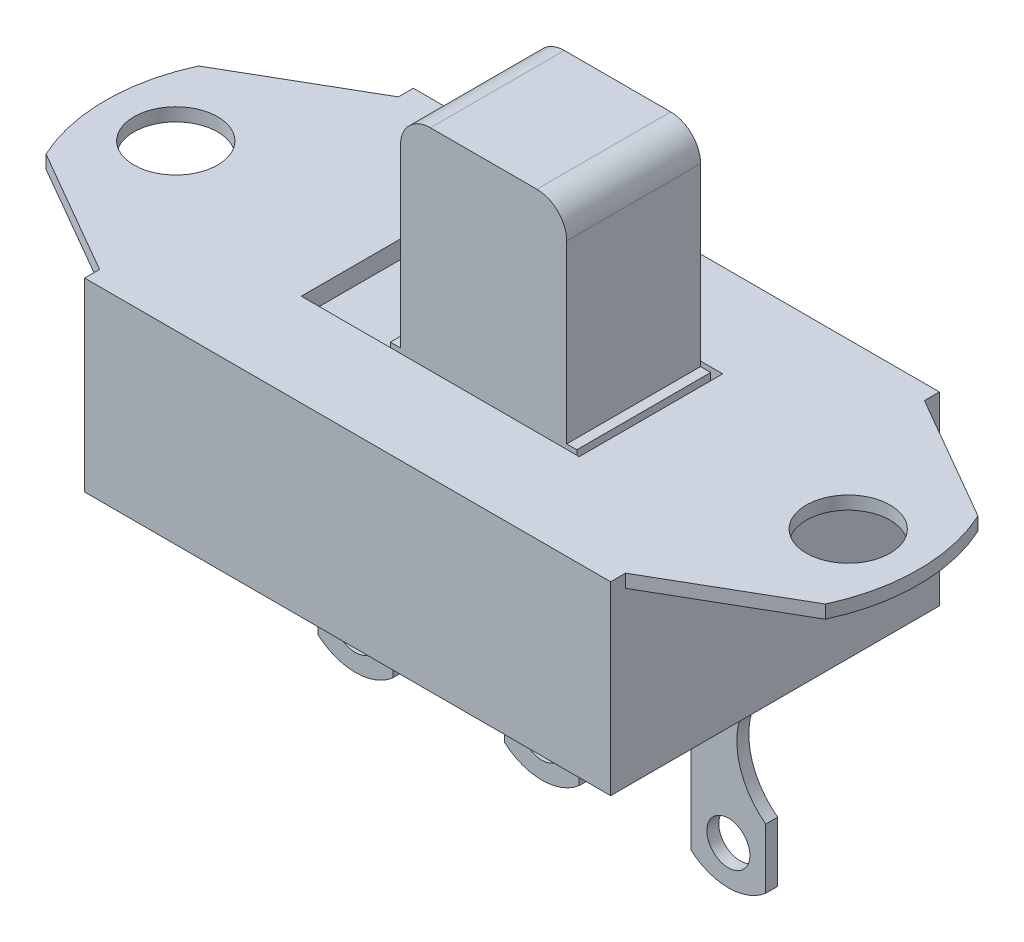
SolidWorks part; units mm, degrees
ref_plane "Front Plane" through (0, 0, 0) normal (0, 0, 1) x (1, 0, 0)
ref_plane "Top Plane" through (0, 0, 0) normal (0, 1, 0) x (1, 0, 0)
ref_plane "Right Plane" through (0, 0, 0) normal (1, 0, 0) x (0, 0, -1)
sketch "Sketch1" plane through (0, 0, 0) normal (0, 0, 1) x (1, 0, 0)
  line L1 (0, 0) -> (22.352, 0)
  line L2 (0, 0) -> (0, 7.874)
  line L3 (0, 7.874) -> (22.352, 7.874)
  line L4 (22.352, 0) -> (22.352, 7.874)
  dimension "D1" = 22.352
  dimension "D2" = 7.874
extrude "Extrude1" add sketch "Sketch1" along normal mid plane 13.97
sketch "Sketch2" plane through (0, 7.874, 0) normal (0, 1, 0) x (1, 0, 0)
  line L0 (0, 6.35) -> (-5.3848, 3.2411)
  line L1 (0, -6.985) -> (0, 6.985) construction
  line L2 (-6.096, 6.4274) -> (-6.096, -6.7131) construction
  line L3 (11.176, 6.985) -> (11.176, -6.985) construction
  line L4 (22.352, 6.985) -> (0, 6.985) construction
  line L5 (22.352, -6.985) -> (0, -6.985) construction
  line L6 (0, 0) -> (-8.6981, 0) construction
  line L7 (0, -6.35) -> (-5.3848, -3.2411)
  line L8 (0, 6.35) -> (0, -6.35)
  line L9 (22.352, 6.35) -> (22.352, -6.35)
  line L10 (22.352, -6.35) -> (27.7368, -3.2411)
  line L11 (22.352, 6.35) -> (27.7368, 3.2411)
  arc A0 (-5.3848, 3.2411) -> (-5.3848, -3.2411) centre (1.6447, 0) ccw
  arc A1 (27.7368, 3.2411) -> (27.7368, -3.2411) centre (20.7073, 0) cw
  dimension "D1" = 17.272
  dimension "D2" = 30
  dimension "D3" = 6.35
  dimension "D4" = 5.3848
extrude "Extrude2" add sketch "Sketch2" against normal blind 0.5588
sketch "Sketch3" plane through (0, 7.874, 0) normal (0, 1, 0) x (1, 0, 0)
  line L0 (11.176, 6.985) -> (11.176, -6.985) construction
  line L1 (22.352, 6.985) -> (0, 6.985) construction
  line L2 (22.352, -6.985) -> (0, -6.985) construction
  line L3 (0, 0) -> (23.8748, 0) construction
  line L5 (5.2705, 3.048) -> (17.0815, 3.048)
  line L6 (5.2705, 3.048) -> (5.2705, -3.048)
  line L7 (5.2705, -3.048) -> (17.0815, -3.048)
  line L8 (17.0815, 3.048) -> (17.0815, -3.048)
  dimension "D1" = 6.096
  dimension "D2" = 11.811
extrude "Extrude3" cut sketch "Sketch3" against normal blind 0.762
sketch "Sketch4" plane through (0, 7.112, 0) normal (0, 1, 0) x (1, 0, 0)
  line L0 (5.2705, 0) -> (17.0815, 0) construction
  line L1 (9.2837, 2.8448) -> (16.3449, 2.8448)
  line L2 (9.2837, 2.8448) -> (9.2837, -2.8448)
  line L3 (9.2837, -2.8448) -> (16.3449, -2.8448)
  line L4 (16.3449, 2.8448) -> (16.3449, -2.8448)
  line L5 (5.2705, 3.048) -> (5.2705, -3.048) construction
  line L6 (17.0815, -3.048) -> (17.0815, 3.048) construction
  dimension "D1" = 5.6896
  dimension "D2" = 7.0612
  dimension "D3" = 9.2837
extrude "Extrude4" add sketch "Sketch4" along normal blind 9.4996
sketch "Sketch7" plane through (0, 7.874, 0) normal (0, 1, 0) x (1, 0, 0)
  line L0 (12.8143, 2.8448) -> (12.8143, -2.8448) construction
  line L1 (8.8519, 2.8448) -> (16.7767, 2.8448)
  line L2 (8.8519, 2.8448) -> (8.8519, -2.8448)
  line L3 (8.8519, -2.8448) -> (16.7767, -2.8448)
  line L4 (16.7767, 2.8448) -> (16.7767, -2.8448)
  line L5 (16.3449, 2.8448) -> (9.2837, 2.8448) construction
  line L6 (9.2837, -2.8448) -> (16.3449, -2.8448) construction
  dimension "D1" = 7.9248
extrude "Extrude7" add sketch "Sketch7" against normal up to surface (0.762 mm away) up to face at (11.176, 7.112, 0)
fillet "Fillet2" radius 1.27 2 edges at (16.3449, 16.6116, 0) (9.2837, 16.6116, 0)
sketch "Sketch5" plane through (0, 7.874, 0) normal (0, 1, 0) x (1, 0, 0)
  line L0 (11.176, 6.985) -> (11.176, -6.985) construction
  line L1 (22.352, 6.985) -> (0, 6.985) construction
  line L2 (22.352, -6.985) -> (0, -6.985) construction
  circle A0 centre (-3.1115, 0) radius 1.778
  circle A1 centre (25.4635, 0) radius 1.778
  dimension "D2" = 3.556
  dimension "D1" = 28.575
extrude "Extrude5" cut sketch "Sketch5" against normal blind 9.4996
ref_plane "Plane1" through (0, 0, -1.27) normal (0, 0, 1) x (1, 0, 0)
sketch "Sketch6" plane through (0, 0, -1.27) normal (0, 0, 1) x (1, 0, 0)
  line L0 (11.176, 0) -> (11.176, -9.144) construction
  line L1 (0, 0) -> (22.352, 0) construction
  line L2 (12.7635, -6.0021) -> (12.7635, -8.5483)
  line L3 (9.5885, 0) -> (12.7635, 0)
  line L4 (9.5885, 0) -> (9.5885, -8.5483)
  line L6 (12.7635, 0) -> (12.7635, -1.1099)
  arc A0 (9.5885, -8.5483) -> (12.7635, -8.5483) centre (11.176, -6.731) ccw
  circle A1 centre (11.176, -7.493) radius 0.9144
  arc A2 (12.7635, -1.1099) -> (12.7635, -6.0021) centre (14.582, -3.556) ccw
  dimension "D4" = 1.8288
  dimension "D7" = 3.048
  dimension "D1" = 3.175
  dimension "D2" = 9.144
  dimension "D3" = 2.413
  dimension "D5" = 1.651
  dimension "D6" = 3.937
extrude "Extrude6" add sketch "Sketch6" against normal blind 0.508
pattern_linear "LPattern1" count 2 spacing 7.9248 along (1, 0, 0) of "Extrude6"
pattern_linear "LPattern2" count 2 spacing 7.9248 along (-1, 0, 0) of "Extrude6"
sketch "Sketch8" [suppressed] plane through (0, 7.874, 0) normal (0, 1, 0) x (1, 0, 0)
  line L0 (12.7635, 5.7156) -> (12.7635, -4.5769)
  line L1 (5.2705, 3.048) -> (5.2705, -3.048) construction
  dimension "D1" = 7.493
ref_plane "Plane2" [suppressed] through (12.7762, 0, 0) normal (1, 0, 0) x (0, 0, -1)
